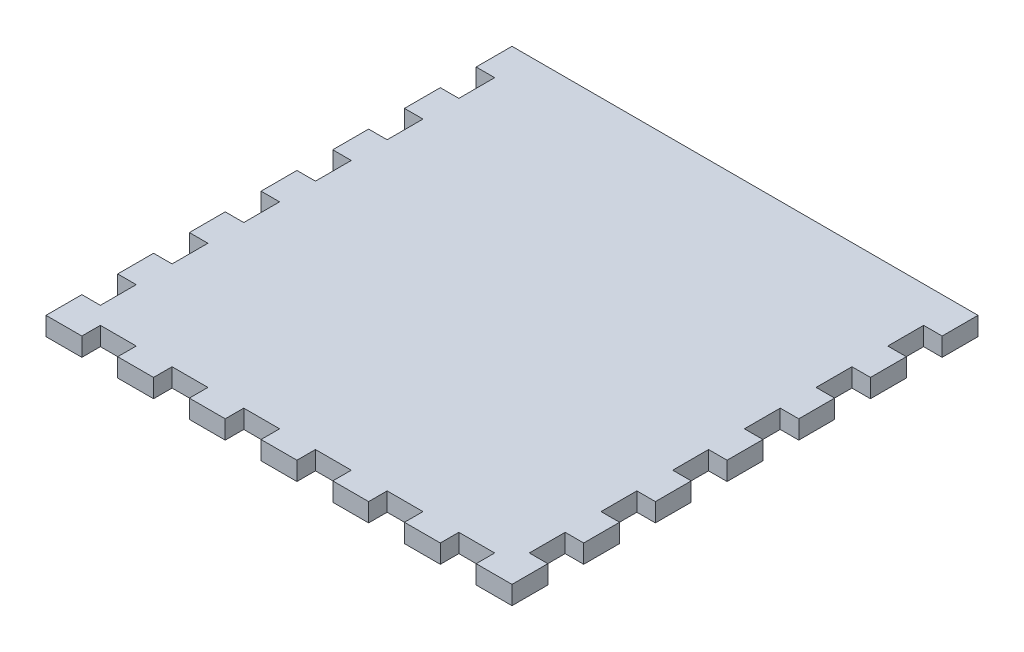
SolidWorks part; units mm, degrees
material "Acrylic (Medium-high impact)"
ref_plane "Front Plane" through (0, 0, 0) normal (0, 0, 1) x (1, 0, 0)
ref_plane "Top Plane" through (0, 0, 0) normal (0, 1, 0) x (1, 0, 0)
ref_plane "Right Plane" through (0, 0, 0) normal (1, 0, 0) x (0, 0, -1)
sketch "Sketch1" plane through (0, 0, 0) normal (0, 1, 0) x (1, 0, 0)
  line L1 (-40, -40) -> (40, -40)
  line L2 (-40, -40) -> (-40, 40)
  line L3 (-40, 40) -> (40, 40)
  line L4 (40, -40) -> (40, 40)
  line L5 (-40, -40) -> (40, 40) construction
  line L6 (-40, 40) -> (40, -40) construction
  point P0 (0, 0)
  dimension "D1" = 80
extrude "Boss-Extrude1" add sketch "Sketch1" along normal mid plane 3.175
sketch "Sketch2" plane through (0, 1.5875, 0) normal (0, 1, 0) x (1, 0, 0)
  line L0 (0, 0) -> (50000, 0) construction
  line L1 (40, -40) -> (40, 40) construction
  line L2 (0, 0) -> (0, -50000) construction
  line L3 (-40, -40) -> (40, -40) construction
  line L4 (-40, 40) -> (-40, 33.8462)
  line L5 (-40, 40) -> (-40, -40) construction
  line L6 (-40, 33.8462) -> (-36.82, 33.8462)
  line L7 (-36.82, 33.8462) -> (-36.82, 27.6923)
  line L8 (-36.82, 27.6923) -> (-40, 27.6923)
  line L9 (-36.82, 15.3846) -> (-40, 15.3846)
  line L10 (-36.82, 21.5385) -> (-36.82, 15.3846)
  line L11 (-40, 21.5385) -> (-36.82, 21.5385)
  line L12 (-40, 27.6923) -> (-40, 21.5385)
  line L13 (-36.82, 3.0769) -> (-40, 3.0769)
  line L14 (-36.82, 9.2308) -> (-36.82, 3.0769)
  line L15 (-40, 9.2308) -> (-36.82, 9.2308)
  line L16 (-40, 15.3846) -> (-40, 9.2308)
  line L17 (-36.82, -9.2308) -> (-40, -9.2308)
  line L18 (-36.82, -3.0769) -> (-36.82, -9.2308)
  line L19 (-40, -3.0769) -> (-36.82, -3.0769)
  line L20 (-40, 3.0769) -> (-40, -3.0769)
  line L21 (-36.82, -21.5385) -> (-40, -21.5385)
  line L22 (-36.82, -15.3846) -> (-36.82, -21.5385)
  line L23 (-40, -15.3846) -> (-36.82, -15.3846)
  line L24 (-40, -9.2308) -> (-40, -15.3846)
  line L25 (-36.82, -33.8462) -> (-40, -33.8462)
  line L26 (-36.82, -27.6923) -> (-36.82, -33.8462)
  line L27 (-40, -27.6923) -> (-36.82, -27.6923)
  line L28 (-40, -21.5385) -> (-40, -27.6923)
  line L29 (-40, -33.8462) -> (-40, -40)
  line L30 (40, -33.8462) -> (40, -40)
  line L31 (40, -21.5385) -> (40, -27.6923)
  line L32 (40, -27.6923) -> (36.82, -27.6923)
  line L33 (36.82, -27.6923) -> (36.82, -33.8462)
  line L34 (36.82, -33.8462) -> (40, -33.8462)
  line L35 (40, -9.2308) -> (40, -15.3846)
  line L36 (40, -15.3846) -> (36.82, -15.3846)
  line L37 (36.82, -15.3846) -> (36.82, -21.5385)
  line L38 (36.82, -21.5385) -> (40, -21.5385)
  line L39 (40, 3.0769) -> (40, -3.0769)
  line L40 (40, -3.0769) -> (36.82, -3.0769)
  line L41 (36.82, -3.0769) -> (36.82, -9.2308)
  line L42 (36.82, -9.2308) -> (40, -9.2308)
  line L43 (40, 15.3846) -> (40, 9.2308)
  line L44 (40, 9.2308) -> (36.82, 9.2308)
  line L45 (36.82, 9.2308) -> (36.82, 3.0769)
  line L46 (36.82, 3.0769) -> (40, 3.0769)
  line L47 (40, 27.6923) -> (40, 21.5385)
  line L48 (40, 21.5385) -> (36.82, 21.5385)
  line L49 (36.82, 21.5385) -> (36.82, 15.3846)
  line L50 (36.82, 15.3846) -> (40, 15.3846)
  line L51 (36.82, 27.6923) -> (40, 27.6923)
  line L52 (36.82, 33.8462) -> (36.82, 27.6923)
  line L53 (40, 33.8462) -> (36.82, 33.8462)
  line L54 (40, 40) -> (40, 33.8462)
  line L55 (-40, 40) -> (-33.8462, 40)
  line L56 (40, 40) -> (-40, 40) construction
  line L57 (-33.8462, 40) -> (-33.8462, 36.82)
  line L58 (-33.8462, 36.82) -> (-27.6923, 36.82)
  line L59 (-27.6923, 36.82) -> (-27.6923, 40)
  line L60 (-27.6923, 40) -> (-21.5385, 40)
  line L61 (-21.5385, 40) -> (-21.5385, 36.82)
  line L62 (-21.5385, 36.82) -> (-15.3846, 36.82)
  line L63 (-15.3846, 36.82) -> (-15.3846, 40)
  line L64 (-15.3846, 40) -> (-9.2308, 40)
  line L65 (-9.2308, 40) -> (-9.2308, 36.82)
  line L66 (-9.2308, 36.82) -> (-3.0769, 36.82)
  line L67 (-3.0769, 36.82) -> (-3.0769, 40)
  line L68 (-3.0769, 40) -> (3.0769, 40)
  line L69 (3.0769, 40) -> (3.0769, 36.82)
  line L70 (3.0769, 36.82) -> (9.2308, 36.82)
  line L71 (9.2308, 36.82) -> (9.2308, 40)
  line L72 (9.2308, 40) -> (15.3846, 40)
  line L73 (15.3846, 40) -> (15.3846, 36.82)
  line L74 (15.3846, 36.82) -> (21.5385, 36.82)
  line L75 (21.5385, 36.82) -> (21.5385, 40)
  line L76 (21.5385, 40) -> (27.6923, 40)
  line L77 (27.6923, 40) -> (27.6923, 36.82)
  line L78 (27.6923, 36.82) -> (33.8462, 36.82)
  line L79 (33.8462, 36.82) -> (33.8462, 40)
  line L80 (33.8462, 40) -> (40, 40)
  line L81 (-40, -40) -> (-33.8462, -40)
  line L82 (33.8462, -40) -> (40, -40)
  line L83 (33.8462, -36.82) -> (33.8462, -40)
  line L84 (27.6923, -36.82) -> (33.8462, -36.82)
  line L85 (27.6923, -40) -> (27.6923, -36.82)
  line L86 (21.5385, -40) -> (27.6923, -40)
  line L87 (21.5385, -36.82) -> (21.5385, -40)
  line L88 (15.3846, -36.82) -> (21.5385, -36.82)
  line L89 (15.3846, -40) -> (15.3846, -36.82)
  line L90 (9.2308, -40) -> (15.3846, -40)
  line L91 (9.2308, -36.82) -> (9.2308, -40)
  line L92 (3.0769, -36.82) -> (9.2308, -36.82)
  line L93 (3.0769, -40) -> (3.0769, -36.82)
  line L94 (-3.0769, -40) -> (3.0769, -40)
  line L95 (-3.0769, -36.82) -> (-3.0769, -40)
  line L96 (-9.2308, -36.82) -> (-3.0769, -36.82)
  line L97 (-9.2308, -40) -> (-9.2308, -36.82)
  line L98 (-15.3846, -40) -> (-9.2308, -40)
  line L99 (-15.3846, -36.82) -> (-15.3846, -40)
  line L100 (-21.5385, -36.82) -> (-15.3846, -36.82)
  line L101 (-21.5385, -40) -> (-21.5385, -36.82)
  line L102 (-27.6923, -40) -> (-21.5385, -40)
  line L103 (-27.6923, -36.82) -> (-27.6923, -40)
  line L104 (-33.8462, -36.82) -> (-27.6923, -36.82)
  line L105 (-33.8462, -40) -> (-33.8462, -36.82)
  point P5 (40, 0)
  point P10 (0, -40)
  dimension "D1" = 3.18
  dimension "D2" = 3.18
  dimension "D3" = 6
  dimension "D6" = 6
extrude "Cut-Extrude1" cut sketch "Sketch2" against normal through all flip side to cut
sketch "Sketch3" plane through (0, 1.5875, 0) normal (0, 1, 0) x (1, 0, 0)
  line L0 (-40, 40) -> (40, 40)
  line L1 (40, 40) -> (40, 33.8462)
  line L2 (40, 33.8462) -> (-40, 33.8462)
  line L3 (-40, 33.8462) -> (-40, 40)
extrude "Boss-Extrude2" add sketch "Sketch3" against normal up to surface (3.175 mm away) up to face at (0, -1.5875, 0)
